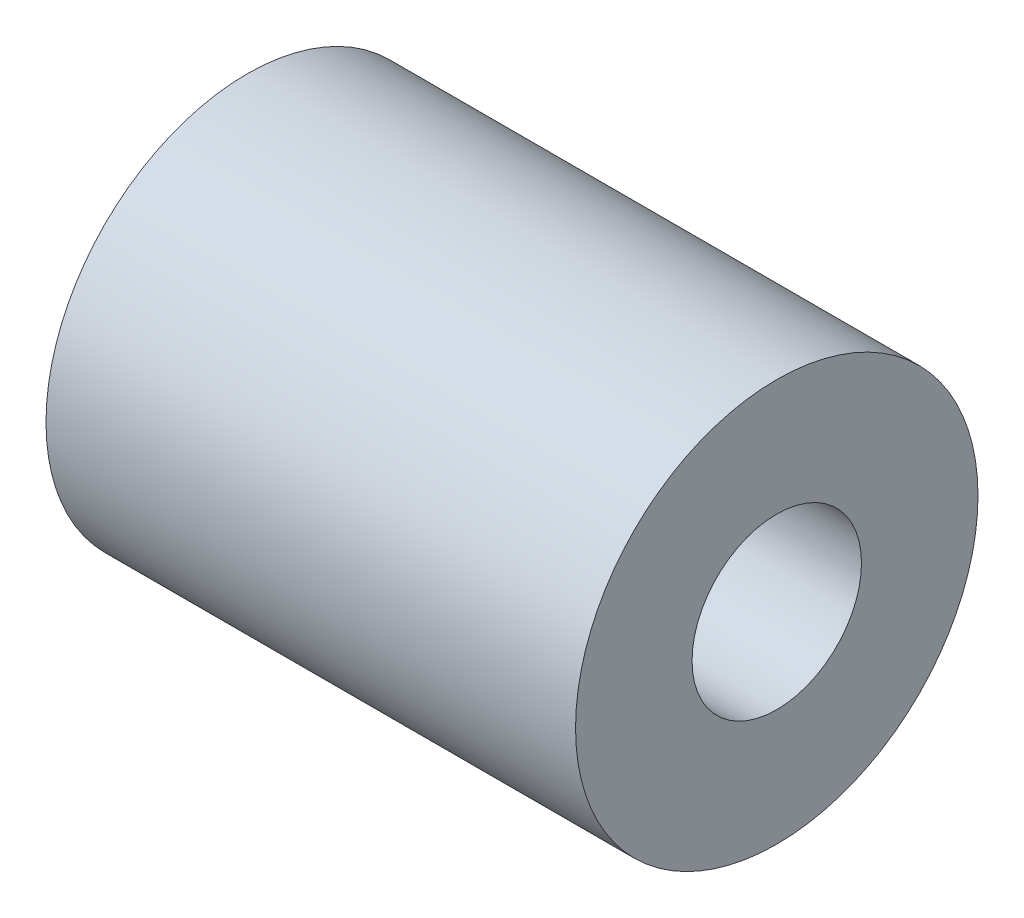
SolidWorks part; units mm, degrees
ref_plane "前视基准面" through (0, 0, 0) normal (0, 0, 1) x (1, 0, 0)
ref_plane "上视基准面" through (0, 0, 0) normal (0, 1, 0) x (1, 0, 0)
ref_plane "右视基准面" through (0, 0, 0) normal (1, 0, 0) x (0, 0, -1)
sketch "草图1" plane through (0, 0, 0) normal (1, 0, 0) x (0, 0, -1)
  circle A0 centre (0, 0) radius 9.5
  dimension "D1" = 19
extrude "凸台-拉伸1" add sketch "草图1" along normal blind 25
sketch "草图2" plane through (0, 0, 0) normal (-1, 0, 0) x (0, 0, 1)
  circle A0 centre (0, 0) radius 2.5
  dimension "D1" = 5
extrude "切除-拉伸1" cut sketch "草图2" against normal blind 12.5
sketch "草图3" plane through (25, 0, 0) normal (1, 0, 0) x (0, 0, -1)
  circle A0 centre (0, 0) radius 4
  dimension "D1" = 8
extrude "切除-拉伸2" cut sketch "草图3" against normal blind 12.5
